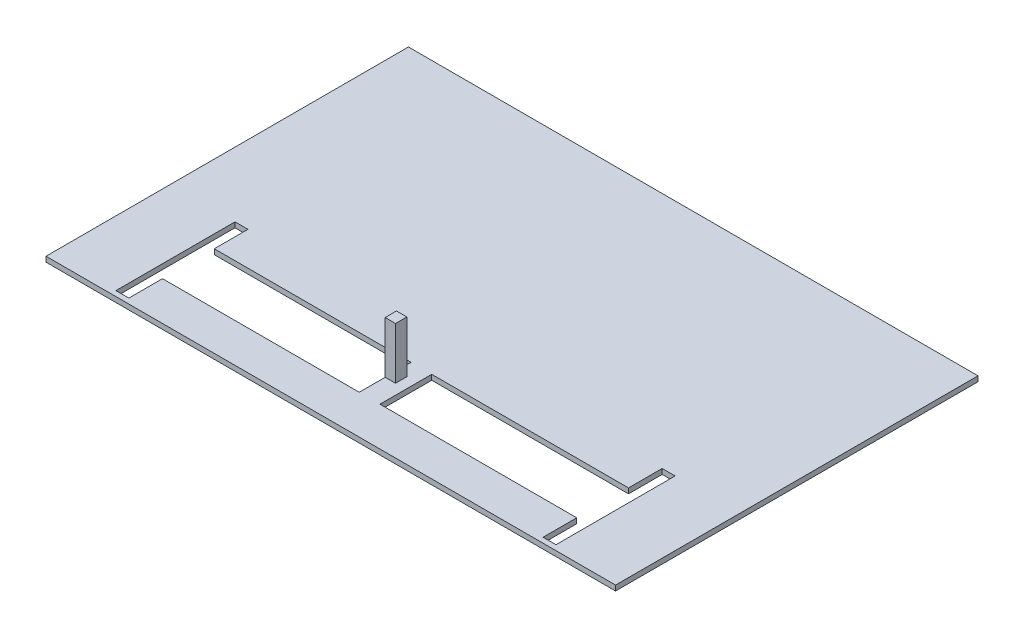
SolidWorks part; units mm, degrees
ref_plane "Front Plane" through (0, 0, 0) normal (0, 0, 1) x (1, 0, 0)
ref_plane "Top Plane" through (0, 0, 0) normal (0, 1, 0) x (1, 0, 0)
ref_plane "Right Plane" through (0, 0, 0) normal (1, 0, 0) x (0, 0, -1)
sketch "Sketch2" plane through (0, 0, 0) normal (0, 1, 0) x (1, 0, 0)
  line L0 (-110, -45) -> (110, -45) construction
  line L1 (110, -70) -> (-110, -70)
  line L2 (110, -70) -> (110, 70)
  line L3 (110, 70) -> (-110, 70)
  line L4 (-110, -70) -> (-110, 70)
  line L5 (110, -70) -> (-110, 70) construction
  line L6 (110, 70) -> (-110, -70) construction
  line L7 (0, 70) -> (0, -70) construction
  point P0 (0, 0)
  dimension "D1" = 140
  dimension "D2" = 220
  dimension "D3" = 115
extrude "Boss-Extrude1" add sketch "Sketch2" along normal blind 2
sketch "Sketch3" plane through (0, 0, 0) normal (0, 1, 0) x (1, 0, 0)
  line L0 (-110, -45) -> (110, -45) construction
  line L1 (-110, 70) -> (-110, -70) construction
  line L2 (110, -70) -> (110, 70) construction
  line L3 (110, 70) -> (-110, 70) construction
  line L4 (0, 70) -> (0, -70) construction
  line L5 (-110, -70) -> (110, -70) construction
  line L6 (-80, -35) -> (-80, -22)
  line L7 (80, -55) -> (-80, -55)
  line L9 (80, -35) -> (-80, -35)
  line L11 (80, -55) -> (-80, -35) construction
  line L12 (80, -35) -> (-80, -55) construction
  line L13 (-80, -22) -> (-85, -22)
  line L14 (-85, -22) -> (-85, -68)
  line L17 (-80, -68) -> (-85, -68)
  line L18 (-80, -55) -> (-80, -68)
  line L19 (80, -55) -> (80, -68)
  line L20 (80, -68) -> (85, -68)
  line L21 (85, -22) -> (85, -68)
  line L22 (80, -22) -> (85, -22)
  line L23 (80, -35) -> (80, -22)
  point P12 (0, -45)
  point P21 (-85, -45)
  dimension "D1" = 115
  dimension "D2" = 160
  dimension "D3" = 20
  dimension "D4" = 13
  dimension "D5" = 5
extrude "Cut-Extrude1" cut sketch "Sketch3" along normal blind 2
sketch "Sketch4" plane through (0, 0, 0) normal (0, 1, 0) x (1, 0, 0)
  line L0 (0, 70) -> (0, -70) construction
  line L1 (110, 70) -> (-110, 70) construction
  line L2 (-110, -70) -> (110, -70) construction
  line L3 (-110, -45) -> (110, -45) construction
  line L4 (-110, 70) -> (-110, -70) construction
  line L5 (110, -70) -> (110, 70) construction
  line L7 (4, -55) -> (-4, -55)
  line L8 (4, -55) -> (4, -35)
  line L9 (4, -35) -> (-4, -35)
  line L10 (-4, -55) -> (-4, -35)
  line L11 (4, -55) -> (-4, -35) construction
  line L12 (4, -35) -> (-4, -55) construction
  point P12 (0, -45)
  dimension "D1" = 115
  dimension "D2" = 8
  dimension "D3" = 20
extrude "Boss-Extrude2" add sketch "Sketch4" along normal blind 2
ref_plane "Plane1" through (0, 2, 0) normal (0, 1, 0) x (1, 0, 0)
sketch "Sketch5" plane through (0, 2, 0) normal (0, 1, 0) x (1, 0, 0)
  line L0 (0, 0) -> (0, -70) construction
  line L1 (-110, -70) -> (110, -70) construction
  line L2 (-110, -45) -> (110, -45) construction
  line L3 (-110, 70) -> (-110, -70) construction
  line L4 (110, -70) -> (110, 70) construction
  line L5 (-4, -35) -> (-4, -55) construction
  line L6 (0, -45) -> (-4, -45)
  line L7 (0, -45) -> (0, -40.6188)
  line L8 (0, -40.6188) -> (-4, -40.6188)
  line L9 (-4, -45) -> (-4, -40.6188)
  dimension "D1" = 115
extrude "Boss-Extrude3" add sketch "Sketch5" along normal blind 20
